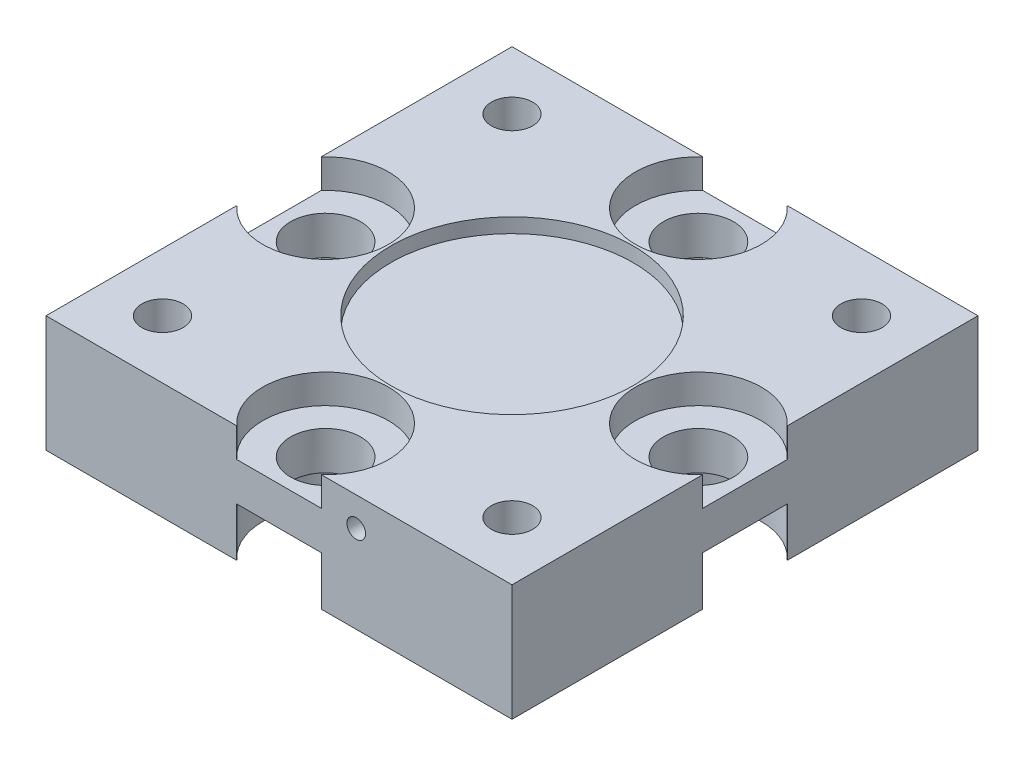
SolidWorks part; units mm, degrees
material "Copper"
ref_plane "Front Plane" through (0, 0, 0) normal (0, 0, 1) x (1, 0, 0)
ref_plane "Top Plane" through (0, 0, 0) normal (0, 1, 0) x (1, 0, 0)
ref_plane "Right Plane" through (0, 0, 0) normal (1, 0, 0) x (0, 0, -1)
sketch "Sketch1" plane through (0, 0, 0) normal (0, 1, 0) x (1, 0, 0)
  line L1 (-25.4, 25.4) -> (25.4, 25.4)
  line L2 (-25.4, 25.4) -> (-25.4, -25.4)
  line L3 (-25.4, -25.4) -> (25.4, -25.4)
  line L4 (25.4, 25.4) -> (25.4, -25.4)
  dimension "D1" = 50.8
  dimension "D2" = 50.8
  dimension "D3" = 25.4
  dimension "D4" = 25.4
extrude "Boss-Extrude1" add sketch "Sketch1" along normal blind 12.7
hole_wizard "#8 Clearance Hole1" positions "Sketch4" profile "Sketch3" hole size "#8" standard "ANSI Inch" end condition through all
sketch "Sketch4" plane through (0, 12.7, 0) normal (0, 1, 0) x (1, 0, 0)
  line L0 (-25.4, 25.4) -> (-25.4, -25.4) construction
  line L1 (25.4, 25.4) -> (-25.4, 25.4) construction
  line L2 (25.4, -25.4) -> (25.4, 25.4) construction
  line L3 (-25.4, -25.4) -> (25.4, -25.4) construction
  point P0 (-19.05, -19.05)
  point P2 (-19.05, 19.05)
  point P4 (19.05, 19.05)
  point P6 (19.05, -19.05)
  dimension "D1" = 6.35
  dimension "D2" = 6.35
  dimension "D3" = 6.35
  dimension "D4" = 6.35
sketch "Sketch3" plane through (-19.05, 12.7, 19.05) normal (1, 0, 0) x (0, 0, 1)
  line L0 (0, 0) -> (0, 12.7)
  line L1 (0, 12.7) -> (2.2479, 12.7)
  line L2 (2.2479, 12.7) -> (2.2479, 0)
  line L5 (2.2479, 0) -> (0, 0)
  line L11 (0, -6.35) -> (0, 107.95) construction
  dimension "Thru Hole Dia." = 4.4958
  dimension "Thru Hole Depth" = 12.7
sketch "Sketch5" plane through (0, 12.7, 0) normal (0, 1, 0) x (1, 0, 0)
  circle A0 centre (0, 0) radius 13.208
extrude "Cut-Extrude1" cut sketch "Sketch5" against normal blind 1.5875
sketch "Sketch6" plane through (0, 12.7, 0) normal (0, 1, 0) x (1, 0, 0)
  circle A0 centre (0, 20.32) radius 3.81
  circle A1 centre (20.32, 0) radius 3.81
  circle A2 centre (0, -20.32) radius 3.81
  circle A3 centre (-20.32, 0) radius 3.81
  dimension "D1" = 7.62
  dimension "." = 20.32
  dimension "D3" = 20.32
  dimension "D4" = 20.32
  dimension "D5" = 20.32
extrude "Cut-Extrude2" cut sketch "Sketch6" against normal through all
sketch "Sketch10" plane through (0, 12.7, 0) normal (0, 1, 0) x (1, 0, 0)
  circle A0 centre (-20.32, 0) radius 6.858
  circle A1 centre (0, 20.32) radius 6.858
  circle A2 centre (20.32, 0) radius 6.858
  circle A3 centre (0, -20.32) radius 6.858
extrude "Cut-Extrude3" cut sketch "Sketch10" against normal blind 3.175
sketch "Sketch11" plane through (0, 0, 0) normal (0, -1, 0) x (1, 0, 0)
  circle A0 centre (-20.32, 0) radius 6.858
  circle A1 centre (0, 20.32) radius 6.858
  circle A2 centre (20.32, 0) radius 6.858
  circle A3 centre (0, -20.32) radius 6.858
extrude "Cut-Extrude4" cut sketch "Sketch11" against normal blind 5.334
sketch "Sketch12" plane through (0, 0, 25.4) normal (0, 0, 1) x (1, 0, 0)
  line L0 (4.6071, 12.7) -> (25.4, 12.7) construction
  line L1 (4.6071, 12.7) -> (4.6071, 9.525) construction
  circle A0 centre (8.4171, 9.525) radius 1.016
  point P4 (4.6071, 11.1125)
  dimension "D1" = 3.175
  dimension "D2" = 3.81
extrude "Cut-Extrude5" cut sketch "Sketch12" against normal blind 19.05
sketch "Sketch13" plane through (0, 0, -25.4) normal (0, 0, -1) x (-1, 0, 0)
  circle A0 centre (-8.4171, 9.525) radius 1.016
extrude "Cut-Extrude6" cut sketch "Sketch13" against normal blind 19.05
